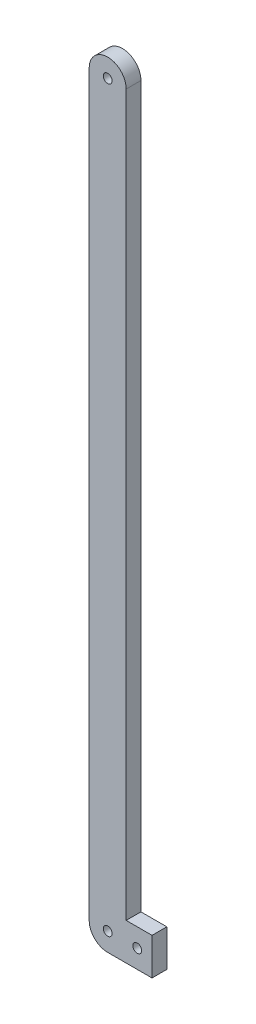
SolidWorks part; units mm, degrees
ref_plane "Front Plane" through (0, 0, 0) normal (0, 0, 1) x (1, 0, 0)
ref_plane "Top Plane" through (0, 0, 0) normal (0, 1, 0) x (1, 0, 0)
ref_plane "Right Plane" through (0, 0, 0) normal (1, 0, 0) x (0, 0, -1)
sketch "Sketch1" plane through (0, 0, 0) normal (0, 0, 1) x (1, 0, 0)
  line L0 (-12.5, 0) -> (-12.5, -499.5998)
  line L1 (12.5, 0) -> (12.5, -487.0998)
  line L2 (-12.5, -249.7999) -> (12.5, -249.7999) construction
  line L3 (0, -512.0998) -> (30, -512.0998)
  line L4 (30, -512.0998) -> (30, -487.0998)
  line L5 (30, -487.0998) -> (12.5, -487.0998)
  line L6 (20, -499.5998) -> (0, 0) construction
  circle A0 centre (0, 0) radius 3
  arc A1 (12.5, 0) -> (-12.5, 0) centre (0, 0) ccw
  arc A2 (0, -512.0998) -> (-12.5, -499.5998) centre (0, -499.5998) cw
  circle A3 centre (0, -499.5998) radius 3
  circle A4 centre (20, -499.5998) radius 3
  dimension "D1" = 6
  dimension "D2" = 25
  dimension "D4" = 20
  dimension "D3" = 500
  dimension "D5" = 10
extrude "Boss-Extrude1" add sketch "Sketch1" along normal blind 10
